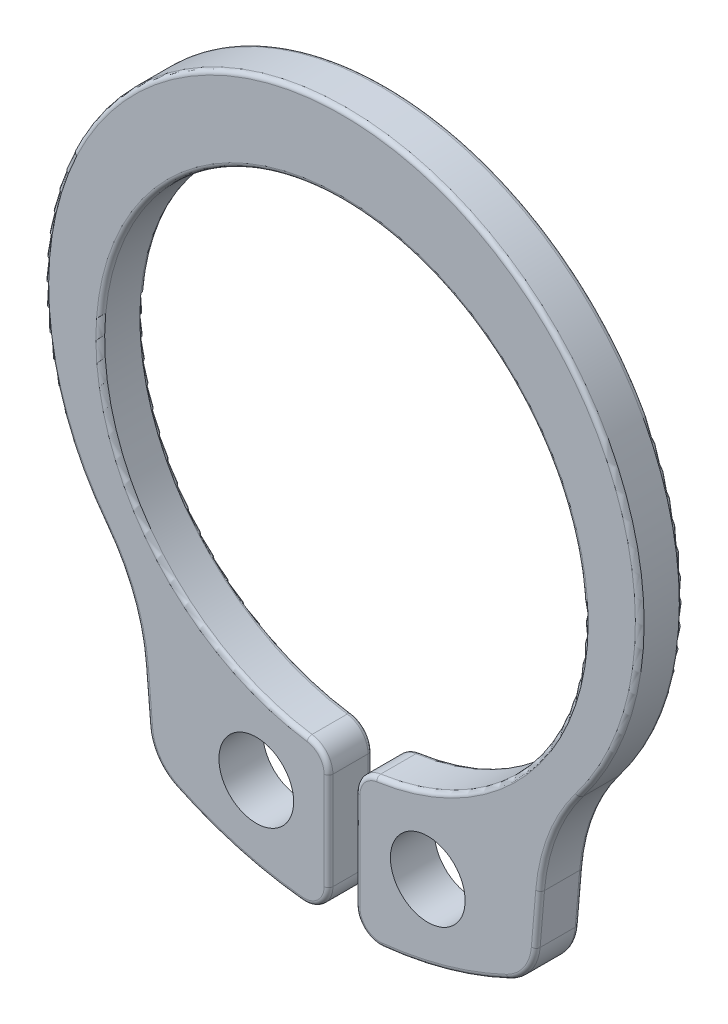
SolidWorks part; units mm, degrees
ref_plane "Front" through (0, 0, 0) normal (0, 0, 1) x (1, 0, 0)
ref_plane "Top" through (0, 0, 0) normal (0, 1, 0) x (1, 0, 0)
ref_plane "Right" through (0, 0, 0) normal (1, 0, 0) x (0, 0, -1)
sketch "Sketch1" plane through (0, 0, 0) normal (0, 0, 1) x (1, 0, 0)
  line L0 (0, 0) -> (-4.7631, -2.75) construction
  line L1 (0, 8.8) -> (0, -8.8) construction
  line L2 (-4.3566, -7.6521) -> (-4.6295, -4.419) construction
  line L4 (-4.6295, -4.419) -> (-5.2806, -5.0404) construction
  line L5 (-4.6295, -4.419) -> (0, 0) construction
  line L6 (0, 5.5) -> (0, 7.3) construction
  line L7 (0, 7.3) -> (0, 6.4) construction
  line L8 (0, -5.5) -> (0, -8.8) construction
  line L9 (-2.4015, -8.4715) -> (0, 0) construction
  line L10 (0, 0) -> (-0.3073, -8.8) construction
  line L11 (-4.3566, -7.6521) -> (0, 0) construction
  line L12 (-4.5352, -5.5364) -> (-5.3819, -3.5874) construction
  line L13 (-4.9586, -4.5619) -> (-4.6295, -4.419) construction
  line L14 (-1.5001, -5.2915) -> (-2.4015, -8.4715) construction
  line L15 (-1.9508, -6.8815) -> (-1.133, -7.1133) construction
  arc A0 (0, 7.3) -> (-4.6295, -4.419) centre (0, 0.5261) ccw construction
  circle A2 centre (0, 0) radius 7.3 construction
  arc A3 (-4.3566, -7.6521) -> (-0.3073, -8.8) centre (0, 0) ccw construction
  circle A4 centre (0, 0) radius 5.5 construction
  circle A6 centre (-1.9508, -6.8815) radius 0.85 construction
  arc A7 (-5.3819, -3.5874) -> (-4.5352, -5.5364) centre (-8.8937, -6.2716) cw construction
  point P5 (-4.7631, -2.75)
  point P24 (-3.6118, -6.3439)
  point P35 (0, 7.3)
  point P36 (0, 5.5)
  point P37 (0, -5.5)
  point P38 (0, -8.8)
  dimension "Ring ID" = 11
  dimension "Hole Diameter" = 1.7
  dimension "D10" = 4.4201
  dimension "Max Sec." = 1.8
  dimension "Lug Height" = 3.3
  dimension "D6" = 2
  dimension "D5" = 3.2446
  dimension "D8" = 2.125
  dimension "D3" = 120
  dimension "D2" = 4.25
  dimension "D4" = 2.125
sketch "Sketch5" plane through (0, 0, 0) normal (0, 1, 0) x (1, 0, 0)
  line L0 (-7.3, 0.5) -> (-7.3, -0.5) construction
  line L2 (0, 0.5) -> (0, -0.5) construction
  line L4 (-7.3, 0) -> (7.3, 0) construction
  point P3 (-7.3, 0)
  point P6 (0, 0)
  dimension "Ring Thickness" = 1
sketch "Sketch2" plane through (0, 0, 0) normal (0, 0, 1) x (1, 0, 0)
  line L0 (-4.3566, -7.6521) -> (-4.6295, -4.419) construction
  line L1 (-4.3566, -7.6521) -> (-4.6295, -4.419)
  line L2 (0, 7.3) -> (0, 5.5)
  line L5 (-0.3073, -8.8) -> (-0.3073, -5.4914)
  arc A0 (0, 7.3) -> (-4.6295, -4.419) centre (0, 0.5261) ccw construction
  arc A1 (-4.3566, -7.6521) -> (-0.3073, -8.8) centre (0, 0) ccw construction
  circle A2 centre (-1.9508, -6.8815) radius 0.85 construction
  arc A4 (0, 7.3) -> (-4.6295, -4.419) centre (0, 0.5261) ccw
  arc A5 (-4.3566, -7.6521) -> (-0.3073, -8.8) centre (0, 0) ccw
  circle A6 centre (-1.9508, -6.8815) radius 0.85
  circle A7 centre (0, 0) radius 5.5 construction
  arc A8 (0, 5.5) -> (-0.3073, -5.4914) centre (0, 0) ccw
extrude "Boss-Extrude1" add sketch "Sketch2" along normal mid plane 1
fillet "Fillet1" radius 4.4201 1 edges at (-4.6295, -4.419, 0)
fillet "Fillet2" radius 1.105 1 edges at (-4.3566, -7.6521, 0)
fillet "Fillet3" radius 0.5525 2 edges at (-0.3073, -8.8, 0) (-0.3073, -5.4914, 0)
mirror "Mirror1" about plane through (0, 7.3, 0.5) normal (-1, 0, 0) of bodies 109
sketch "Sketch3" plane through (0, 0, 0.5) normal (0, 0, 1) x (1, 0, 0)
  line L0 (4.619, -2.9858) -> (5.3923, -3.5738) construction
  line L1 (5.3923, -3.5738) -> (5.9803, -2.8005) construction
  line L2 (0, 7.3) -> (0, 5.5) construction
  circle A0 centre (0, 0) radius 5.5 construction
  arc A1 (5.3923, -3.5738) -> (-5.3923, -3.5738) centre (0, 0.5261) ccw construction
fillet "Fillet4" radius 0.1 32 edges at (-4.457, -6.4623, -0.5) (-4.457, -6.4623, 0.5) (-4.7853, -4.6625, -0.5) (-4.7853, -4.6625, 0.5) (-2.3835, -8.4766, -0.5) (-2.3835, -8.4766, 0.5) (-4.2151, -7.5833, -0.5) (-4.2151, -7.5833, 0.5) (-0.3073, -7.0995, -0.5) (-0.3073, -7.0995, 0.5) (0, 5.5, -0.5) (-0.4423, -5.6293, -0.5) (-0.49, -8.6185, -0.5) (0, 7.3, 0.5) (0, 5.5, 0.5) (-0.4423, -5.6293, 0.5) (-0.49, -8.6185, 0.5) (0.3073, -7.0995, -0.5) (4.457, -6.4623, -0.5) (2.3835, -8.4766, -0.5) (4.457, -6.4623, 0.5) (2.3835, -8.4766, 0.5) (0.3073, -7.0995, 0.5) (4.7853, -4.6625, 0.5) (4.7853, -4.6625, -0.5) (4.2151, -7.5833, 0.5) (4.2151, -7.5833, -0.5) (0.49, -8.6185, 0.5) (0.49, -8.6185, -0.5) (0.4423, -5.6293, 0.5) (0.4423, -5.6293, -0.5) (0, 7.3, -0.5)
equation "\"D1@Fillet1\" = \"D10@Sketch1\""
equation "\"D1@Fillet2\" = \"D10@Sketch1\" / 4"
equation "\"Thickness@Boss-Extrude1\"=\"Ring Thickness@Sketch5\""
equation "\"D2@Sketch1\"=\"Hole Diameter@Sketch1\"*2.5"
equation "\"D4@Sketch1\"=\"D2@Sketch1\"/2"
equation "\"D8@Sketch1\"=\"D4@Sketch1\""
equation "\"D1@Fillet3\"=\"D1@Fillet2\"*.5"
equation "\"D1@Fillet4\"=\"Ring Thickness@Sketch5\"*.1"
